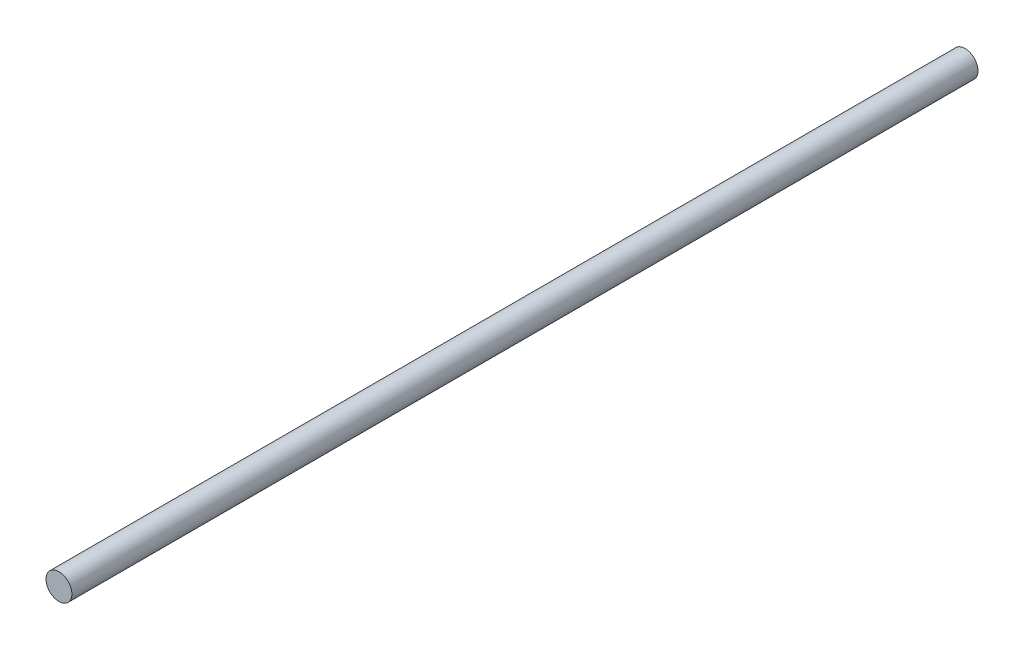
SolidWorks part; units mm, degrees
ref_plane "Plan de face" through (0, 0, 0) normal (0, 0, 1) x (1, 0, 0)
ref_plane "Plan de dessus" through (0, 0, 0) normal (0, 1, 0) x (1, 0, 0)
ref_plane "Plan de droite" through (0, 0, 0) normal (1, 0, 0) x (0, 0, -1)
sketch "Esquisse1" plane through (0, 0, 0) normal (0, 0, 1) x (1, 0, 0)
  circle A0 centre (0, 0) radius 10
  dimension "D1" = 20
extrude "Boss.-Extru.1" add sketch "Esquisse1" along normal blind 700
